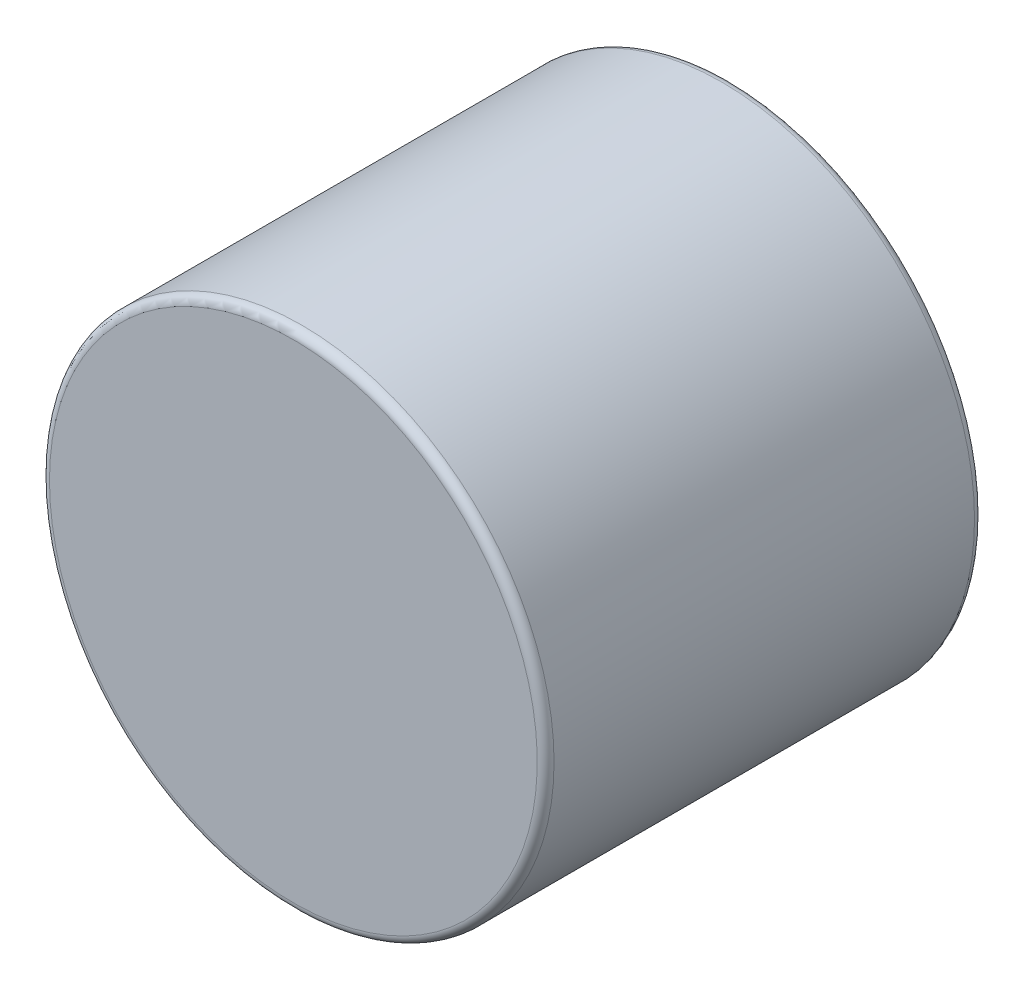
SolidWorks part; units mm, degrees
ref_plane "Front Plane" through (0, 0, 0) normal (0, 0, 1) x (1, 0, 0)
ref_plane "Top Plane" through (0, 0, 0) normal (0, 1, 0) x (1, 0, 0)
ref_plane "Right Plane" through (0, 0, 0) normal (1, 0, 0) x (0, 0, -1)
sketch "Sketch2" plane through (0, 0, 0) normal (1, 0, 0) x (0, 0, -1)
  line L0 (-330.2, 0) -> (330.2, 0) construction
  line L1 (0, 0) -> (0, 37.8362) construction
  line L2 (-330.2, 0) -> (-330.2, 381)
  line L3 (-330.2, 381) -> (330.2, 381)
  line L4 (330.2, 381) -> (330.2, 0)
  line L5 (-325.12, 0) -> (-325.12, 375.92)
  line L6 (-325.12, 375.92) -> (325.12, 375.92)
  line L7 (325.12, 375.92) -> (325.12, 0)
  line L8 (325.12, 0) -> (330.2, 0)
  line L9 (-330.2, 0) -> (-325.12, 0)
  dimension "D1" = 330.2
  dimension "D3" = 381
  dimension "D2" = 5.08
revolve "Revolve1" add sketch "Sketch2" angle 360 about L0
fillet "Fillet1" radius 12.7 2 edges at (381, 0, 330.2) (381, 0, -330.2)
ref_plane "Plane1" through (0, 215.9, 0) normal (0, 1, 0) x (-1, 0, 0)
sketch "Sketch4" plane through (0, 215.9, 0) normal (0, 1, 0) x (-1, 0, 0)
  line L1 (254, 254) -> (-254, 254)
  line L2 (254, 254) -> (254, -254)
  line L3 (254, -254) -> (-254, -254)
  line L4 (-254, 254) -> (-254, -254)
  line L5 (254, 254) -> (-254, -254) construction
  line L6 (254, -254) -> (-254, 254) construction
  point P0 (0, 0)
  dimension "D1" = 508
  dimension "D2" = 508
extrude "Boss-Extrude1" add sketch "Sketch4" along normal blind 6.35 separate body
ref_plane "Plane2" through (0, -292.1, 0) normal (0, 1, 0) x (-1, 0, 0)
sketch "Sketch5" plane through (0, -292.1, 0) normal (0, 1, 0) x (-1, 0, 0)
  line L1 (228.6, 228.6) -> (-228.6, 228.6)
  line L2 (228.6, 228.6) -> (228.6, -228.6)
  line L3 (228.6, -228.6) -> (-228.6, -228.6)
  line L4 (-228.6, 228.6) -> (-228.6, -228.6)
  line L5 (228.6, 228.6) -> (-228.6, -228.6) construction
  line L6 (228.6, -228.6) -> (-228.6, 228.6) construction
  point P0 (0, 0)
  dimension "D1" = 457.2
  dimension "D2" = 457.2
extrude "Boss-Extrude2" add sketch "Sketch5" along normal blind 6.35
